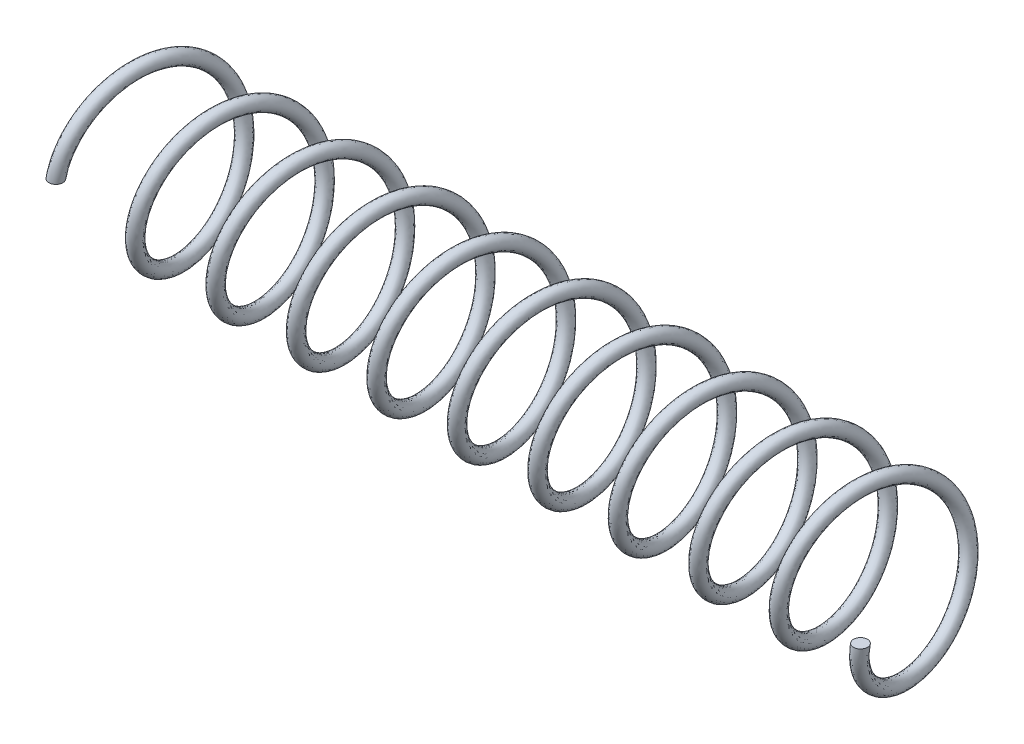
SolidWorks part; units mm, degrees
material "1060 Alloy"
ref_plane "Front Plane" through (0, 0, 0) normal (0, 0, 1) x (1, 0, 0)
ref_plane "Top Plane" through (0, 0, 0) normal (0, 1, 0) x (1, 0, 0)
ref_plane "Right Plane" through (0, 0, 0) normal (1, 0, 0) x (0, 0, -1)
sketch "Sketch1" plane through (0, 0, 0) normal (1, 0, 0) x (0, 0, -1)
  circle A0 centre (0, 0) radius 2.1
  dimension "D1" = 4.2
curve "Helix/Spiral1" pitch 2.3 height 23 turns 10
sketch "Sketch2" plane through (0, 0, 0) normal (0, 1, 0) x (1, 0, 0)
  circle A0 centre (0, -2.1) radius 0.2
  spline S0 degree 3 poles (0, -2.1) (0.0476, -2.1) (0.1439, -1.9907) (0.2875, -1.5236) (0.4313, -0.8246) (0.575, 0) (0.7188, 0.8246) (0.8625, 1.5236) (1.0063, 1.9907) (1.15, 2.1547) (1.2938, 1.9907) (1.4375, 1.5236) (1.6292, 0.5915) (1.8208, -0.5915) (2.0125, -1.5236) (2.1563, -1.9907) (2.3, -2.1547) (2.4438, -1.9907) (2.5875, -1.5236) (2.7792, -0.5915) (2.9708, 0.5915) (3.1625, 1.5236) (3.3062, 1.9907) (3.45, 2.1547) (3.5937, 1.9907) (3.7375, 1.5236) (3.9292, 0.5915) (4.1208, -0.5915) (4.3125, -1.5236) (4.4562, -1.9907) (4.6, -2.1547) (4.7437, -1.9907) (4.8875, -1.5236) (5.0792, -0.5915) (5.2708, 0.5915) (5.4625, 1.5236) (5.6062, 1.9907) (5.75, 2.1547) (5.8937, 1.9907) (6.0375, 1.5236) (6.2292, 0.5915) (6.4208, -0.5915) (6.6125, -1.5236) (6.7562, -1.9907) (6.9, -2.1547) (7.0437, -1.9907) (7.1875, -1.5236) (7.3792, -0.5915) (7.5708, 0.5915) (7.7625, 1.5236) (7.9062, 1.9907) (8.05, 2.1547) (8.1937, 1.9907) (8.3375, 1.5236) (8.5292, 0.5915) (8.7208, -0.5915) (8.9125, -1.5236) (9.0562, -1.9907) (9.2, -2.1547) (9.3437, -1.9907) (9.4875, -1.5236) (9.6792, -0.5915) (9.8708, 0.5915) (10.0625, 1.5236) (10.2062, 1.9907) (10.35, 2.1547) (10.4937, 1.9907) (10.6375, 1.5236) (10.8292, 0.5915) (11.0208, -0.5915) (11.2125, -1.5236) (11.3562, -1.9907) (11.5, -2.1547) (11.6437, -1.9907) (11.7875, -1.5236) (11.9792, -0.5915) (12.1708, 0.5915) (12.3625, 1.5236) (12.5062, 1.9907) (12.65, 2.1547) (12.7937, 1.9907) (12.9375, 1.5236) (13.1292, 0.5915) (13.3208, -0.5915) (13.5125, -1.5236) (13.6562, -1.9907) (13.8, -2.1547) (13.9437, -1.9907) (14.0875, -1.5236) (14.2792, -0.5915) (14.4708, 0.5915) (14.6625, 1.5236) (14.8062, 1.9907) (14.95, 2.1547) (15.0937, 1.9907) (15.2375, 1.5236) (15.4292, 0.5915) (15.6208, -0.5915) (15.8125, -1.5236) (15.9562, -1.9907) (16.1, -2.1547) (16.2437, -1.9907) (16.3875, -1.5236) (16.5792, -0.5915) (16.7708, 0.5915) (16.9625, 1.5236) (17.1062, 1.9907) (17.25, 2.1547) (17.3938, 1.9907) (17.5375, 1.5236) (17.7292, 0.5915) (17.9208, -0.5915) (18.1125, -1.5236) (18.2563, -1.9907) (18.4, -2.1547) (18.5438, -1.9907) (18.6875, -1.5236) (18.8792, -0.5915) (19.0708, 0.5915) (19.2625, 1.5236) (19.4063, 1.9907) (19.55, 2.1547) (19.6938, 1.9907) (19.8375, 1.5236) (20.0292, 0.5915) (20.2208, -0.5915) (20.4125, -1.5236) (20.5562, -1.9907) (20.7, -2.1547) (20.8437, -1.9907) (20.9875, -1.5236) (21.1792, -0.5915) (21.3708, 0.5915) (21.5625, 1.5236) (21.7062, 1.9907) (21.85, 2.1547) (21.9937, 1.9907) (22.1375, 1.5236) (22.2812, 0.8246) (22.425, 0) (22.5687, -0.8246) (22.7125, -1.5236) (22.8561, -1.9907) (22.9524, -2.1) (23, -2.1) knots 0 0 0 0 0.00625 0.0125 0.01875 0.025 0.03125 0.0375 0.04375 0.05 0.05625 0.0625 0.06875 0.08125 0.0875 0.09375 0.1 0.10625 0.1125 0.11875 0.13125 0.1375 0.14375 0.15 0.15625 0.1625 0.16875 0.18125 0.1875 0.19375 0.2 0.20625 0.2125 0.21875 0.23125 0.2375 0.24375 0.25 0.25625 0.2625 0.26875 0.28125 0.2875 0.29375 0.3 0.30625 0.3125 0.31875 0.33125 0.3375 0.34375 0.35 0.35625 0.3625 0.36875 0.38125 0.3875 0.39375 0.4 0.40625 0.4125 0.41875 0.43125 0.4375 0.44375 0.45 0.45625 0.4625 0.46875 0.48125 0.4875 0.49375 0.5 0.50625 0.5125 0.51875 0.53125 0.5375 0.54375 0.55 0.55625 0.5625 0.56875 0.58125 0.5875 0.59375 0.6 0.60625 0.6125 0.61875 0.63125 0.6375 0.64375 0.65 0.65625 0.6625 0.66875 0.68125 0.6875 0.69375 0.7 0.70625 0.7125 0.71875 0.73125 0.7375 0.74375 0.75 0.75625 0.7625 0.76875 0.78125 0.7875 0.79375 0.8 0.80625 0.8125 0.81875 0.83125 0.8375 0.84375 0.85 0.85625 0.8625 0.86875 0.88125 0.8875 0.89375 0.9 0.90625 0.9125 0.91875 0.93125 0.9375 0.94375 0.95 0.95625 0.9625 0.96875 0.975 0.98125 0.9875 0.99375 1 1 1 1 construction
  dimension "D1" = 0.4
sweep "Sweep1" add profiles "Sketch2" path "Helix/Spiral1"
